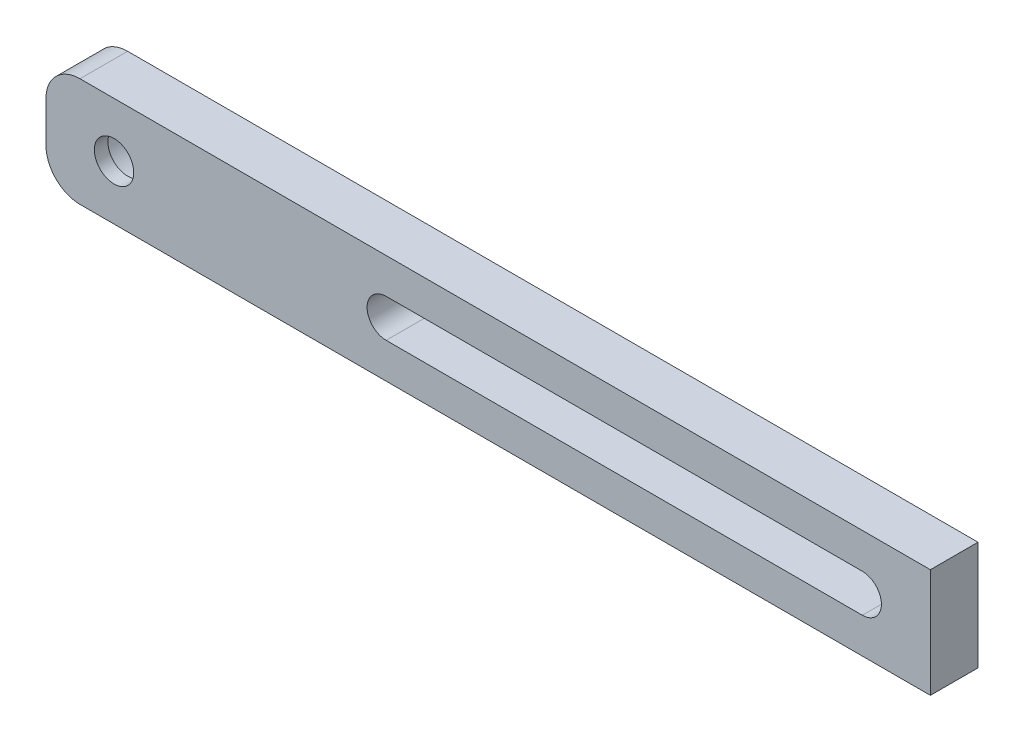
SolidWorks part; units mm, degrees
material "SKD11淬火HRC56-60"
ref_plane "前基準面" through (0, 0, 0) normal (0, 0, 1) x (1, 0, 0)
ref_plane "上基準面" through (0, 0, 0) normal (0, 1, 0) x (1, 0, 0)
ref_plane "右基準面" through (0, 0, 0) normal (1, 0, 0) x (0, 0, -1)
sketch "草图1" plane through (0, 0, 0) normal (0, 0, 1) x (1, 0, 0)
  line L1 (0, 0) -> (130, 0)
  line L2 (0, 0) -> (0, 16)
  line L3 (0, 16) -> (130, 16)
  line L4 (130, 0) -> (130, 16)
  dimension "D1" = 130
  dimension "D2" = 16
extrude "凸台-拉伸1" add sketch "草图1" along normal blind 7
hole_wizard "M5 六角凹头螺钉的柱形沉头孔1" positions "草图3" profile "草图2" counterbore size "M5" standard "ISO" end condition through all
sketch "草图3" plane through (0, 0, 0) normal (0, 0, -1) x (-1, 0, 0)
  line L0 (0, 8) -> (-130, 8) construction
  line L1 (0, 16) -> (0, 0) construction
  line L2 (-130, 0) -> (-130, 16) construction
  point P0 (-10, 8)
  dimension "D1" = 10
sketch "草图2" plane through (10, 8, 0) normal (1, 0, 0) x (0, 1, 0)
  line L0 (0, 0) -> (0, 7)
  line L1 (0, 7) -> (2.9, 7)
  line L3 (2.9, 7) -> (2.9, 5)
  line L4 (2.9, 5) -> (5, 5)
  line L5 (5, 5) -> (5, 0)
  line L7 (5, 0) -> (0, 0)
  line L11 (0, -6.35) -> (0, 107.95) construction
  dimension "通孔孔直径" = 5.8
  dimension "通孔孔深度" = 7
  dimension "柱形沉头孔直径" = 10
  dimension "柱形沉头孔深度" = 5
fillet "圆角1" radius 5 2 edges at (0, 0, 3.5) (0, 16, 3.5)
sketch "草图4" plane through (0, 0, 0) normal (0, 0, -1) x (-1, 0, 0)
  line L0 (-50, 8) -> (-120, 8) construction
  line L1 (-50, 5.2) -> (-120, 5.2)
  line L2 (-50, 10.8) -> (-120, 10.8)
  line L3 (-130, 8) -> (-21.273, 8) construction
  line L4 (-130, 0) -> (-130, 16) construction
  arc A0 (-50, 5.2) -> (-50, 10.8) centre (-50, 8) ccw
  arc A1 (-120, 10.8) -> (-120, 5.2) centre (-120, 8) ccw
  point P2 (-85, 8)
  dimension "D1" = 10
  dimension "D2" = 5.6
  dimension "D3" = 70
extrude "切除-拉伸1" cut sketch "草图4" against normal through all
